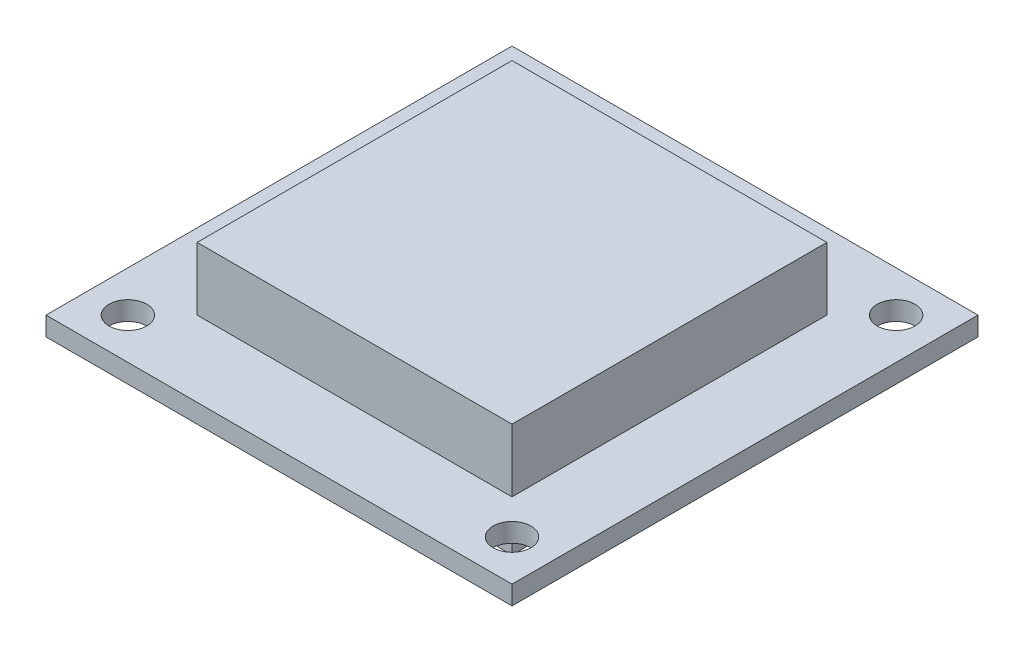
SolidWorks part; units mm, degrees
ref_plane "前视基准面" through (0, 0, 0) normal (0, 0, 1) x (1, 0, 0)
ref_plane "上视基准面" through (0, 0, 0) normal (0, 1, 0) x (1, 0, 0)
ref_plane "右视基准面" through (0, 0, 0) normal (1, 0, 0) x (0, 0, -1)
other "Configuration Table"
sketch "草图1" plane through (0, 0, 0) normal (0, 1, 0) x (1, 0, 0)
  line L1 (-18.5, -18.5) -> (18.5, -18.5)
  line L2 (-18.5, -18.5) -> (-18.5, 18.5)
  line L3 (-18.5, 18.5) -> (18.5, 18.5)
  line L4 (18.5, -18.5) -> (18.5, 18.5)
  line L5 (-18.5, -18.5) -> (18.5, 18.5) construction
  line L6 (-18.5, 18.5) -> (18.5, -18.5) construction
  circle A0 centre (-15.25, 15.25) radius 1.5
  circle A1 centre (15.25, 15.25) radius 1.5
  circle A2 centre (15.25, -15.25) radius 1.5
  circle A3 centre (-15.25, -15.25) radius 1.5
  point P0 (0, 0)
  point P17 (0, 0)
  dimension "D3" = 15.25
  dimension "D4" = 15.25
  dimension "D6" = 3
  dimension "D1" = 37
  dimension "D2" = 37
  dimension "D5" = 4
extrude "凸台-拉伸1" add sketch "草图1" along normal blind 1.5
sketch "草图2" plane through (0, 1.5, 0) normal (0, 1, 0) x (1, 0, 0)
  line L1 (-12.5, -12.5) -> (12.5, -12.5)
  line L2 (-12.5, -12.5) -> (-12.5, 12.5)
  line L3 (-12.5, 12.5) -> (12.5, 12.5)
  line L4 (12.5, -12.5) -> (12.5, 12.5)
  line L5 (-12.5, -12.5) -> (12.5, 12.5) construction
  line L6 (-12.5, 12.5) -> (12.5, -12.5) construction
  point P0 (0, 0)
  dimension "D1" = 25
  dimension "D2" = 25
extrude "凸台-拉伸2" add sketch "草图2" along normal blind 5 and the other way blind 4
